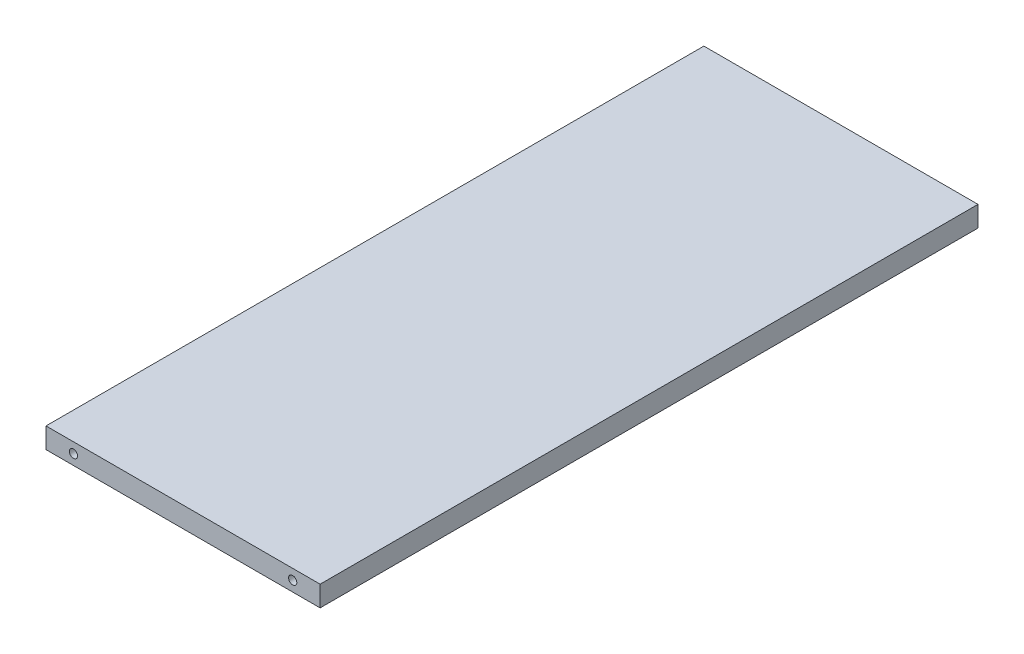
SolidWorks part; units mm, degrees
ref_plane "Front Plane" through (0, 0, 0) normal (0, 0, 1) x (1, 0, 0)
ref_plane "Top Plane" through (0, 0, 0) normal (0, 1, 0) x (1, 0, 0)
ref_plane "Right Plane" through (0, 0, 0) normal (1, 0, 0) x (0, 0, -1)
sketch "Sketch1" plane through (0, 0, 0) normal (0, 1, 0) x (1, 0, 0)
  line L1 (-39.6182, 34.1736) -> (87.3818, 34.1736)
  line L2 (-39.6182, 34.1736) -> (-39.6182, -270.6264)
  line L3 (-39.6182, -270.6264) -> (87.3818, -270.6264)
  line L4 (87.3818, 34.1736) -> (87.3818, -270.6264)
  dimension "D1" = 127
  dimension "D2" = 304.8
extrude "Boss-Extrude1" add sketch "Sketch1" along normal blind 9.525
hole_wizard "#10-24 Tapped Hole1" positions "Sketch3" profile "Sketch2" tap size "#10-24" standard "ANSI Inch"
sketch "Sketch3" plane through (0, 0, 270.6264) normal (0, 0, 1) x (1, 0, 0)
  line L1 (23.8818, 9.525) -> (23.8818, -9.7769) construction
  line L2 (-39.6182, 9.525) -> (87.3818, 9.525) construction
  point P0 (-26.9182, 4.7625)
  point P16 (74.6818, 4.7625)
  dimension "D1" = 101.6
  dimension "D2" = 4.7625
sketch "Sketch2" plane through (-26.9182, 4.7625, 270.6264) normal (1, 0, 0) x (0, -1, 0)
  line L0 (0, 0) -> (0, 25.5248)
  line L1 (0, 25.5248) -> (1.8986, 24.384)
  line L2 (1.8986, 24.384) -> (1.8986, 0)
  line L5 (1.8986, 0) -> (0, 0)
  line L10 (0, 25.5248) -> (-1.8987, 24.384) construction
  line L11 (0, -6.35) -> (0, 107.95) construction
  dimension "Tap Drill Dia." = 3.7973
  dimension "Tap Drill Depth" = 24.384
  dimension "Drill Angle" = 118
cosmetic thread "Hole Thread1" parameters "D1"=19.05, "D2"=4.826
cosmetic thread "Hole Thread2" parameters "D1"=19.05, "D2"=4.826
hole_wizard "#10-24 Tapped Hole2" positions "Sketch5" profile "Sketch4" tap size "#10-24" standard "ANSI Inch"
sketch "Sketch5" plane through (0, 0, -34.1736) normal (0, 0, -1) x (-1, 0, 0)
  line L0 (-23.8818, 9.525) -> (-23.8818, -9.9687) construction
  line L1 (-87.3818, 9.525) -> (39.6182, 9.525) construction
  point P0 (-74.6818, 4.7625)
  point P11 (26.9182, 4.7625)
  dimension "D1" = 4.7625
  dimension "D2" = 101.6
sketch "Sketch4" plane through (74.6818, 4.7625, -34.1736) normal (1, 0, 0) x (0, 1, 0)
  line L0 (0, 0) -> (0, 25.5248)
  line L1 (0, 25.5248) -> (1.8986, 24.384)
  line L2 (1.8986, 24.384) -> (1.8986, 0)
  line L5 (1.8986, 0) -> (0, 0)
  line L10 (0, 25.5248) -> (-1.8987, 24.384) construction
  line L11 (0, -6.35) -> (0, 107.95) construction
  dimension "Tap Drill Dia." = 3.7973
  dimension "Tap Drill Depth" = 24.384
  dimension "Drill Angle" = 118
cosmetic thread "Hole Thread3" parameters "D1"=19.05, "D2"=4.826
cosmetic thread "Hole Thread4" parameters "D1"=19.05, "D2"=4.826
